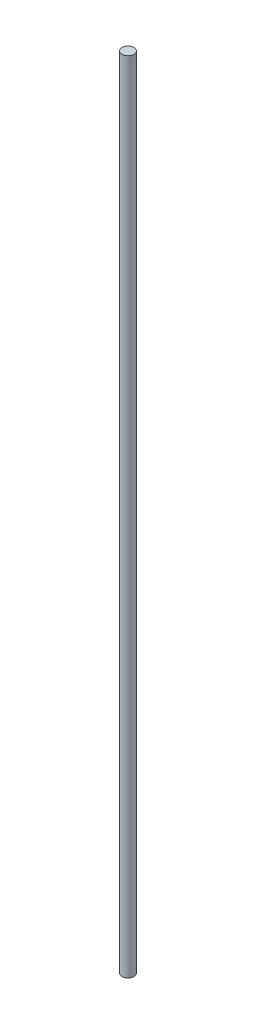
SolidWorks part; units mm, degrees
ref_plane "정면" through (0, 0, 0) normal (0, 0, 1) x (1, 0, 0)
ref_plane "윗면" through (0, 0, 0) normal (0, 1, 0) x (1, 0, 0)
ref_plane "우측면" through (0, 0, 0) normal (1, 0, 0) x (0, 0, -1)
sketch "스케치1" plane through (0, 0, 0) normal (0, 1, 0) x (1, 0, 0)
  circle A0 centre (0, 0) radius 7.5
  dimension "D1" = 15
extrude "보스-돌출1" add sketch "스케치1" along normal blind 1002
